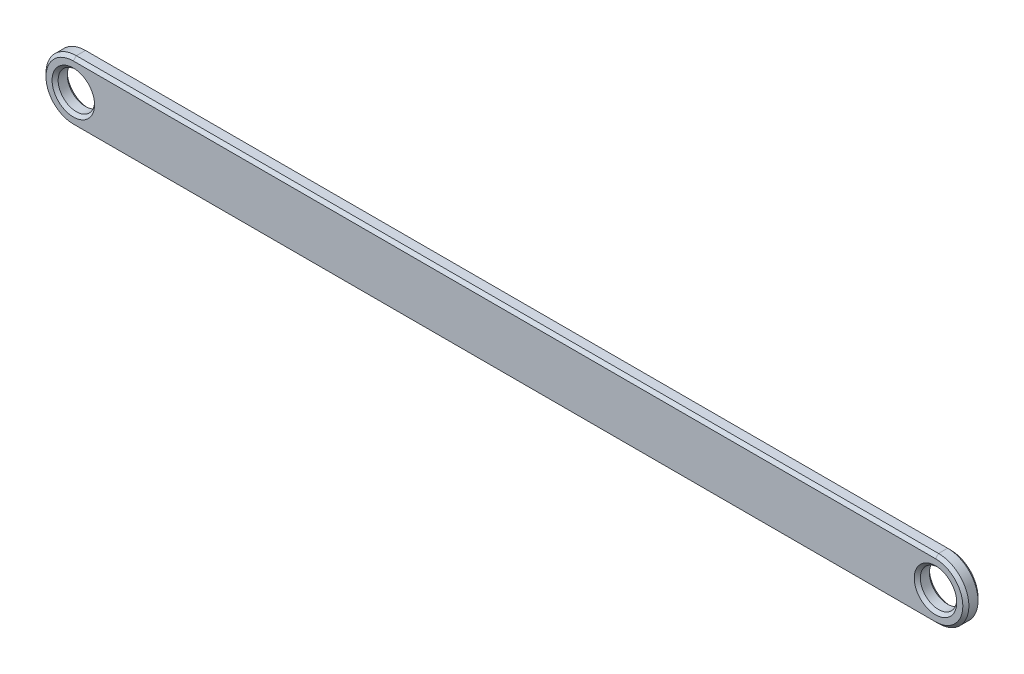
SolidWorks part; units mm, degrees
ref_plane "Front Plane" through (0, 0, 0) normal (0, 0, 1) x (1, 0, 0)
ref_plane "Top Plane" through (0, 0, 0) normal (0, 1, 0) x (1, 0, 0)
ref_plane "Right Plane" through (0, 0, 0) normal (1, 0, 0) x (0, 0, -1)
sketch "Sketch1" plane through (0, 0, 0) normal (0, 0, 1) x (1, 0, 0)
  line L0 (0, 157.4916) -> (0, -223.2358) construction
  line L1 (710, -50) -> (-710, -50)
  line L3 (710, 50) -> (-710, 50)
  line L4 (-710, 0) -> (710, 0) construction
  arc A0 (-710, 50) -> (-710, -50) centre (-710, 0) ccw
  circle A1 centre (-710, 0) radius 30
  arc A2 (710, 50) -> (710, -50) centre (710, 0) cw
  circle A3 centre (710, 0) radius 30
  point P0 (0, 0)
  point P12 (0, 0)
  point P13 (-451.3779, -167.3853)
  point P14 (-602.1707, 50)
  dimension "D1" = 60
  dimension "D2" = 20
  dimension "D3" = 1420
extrude "Boss-Extrude1" add sketch "Sketch1" along normal blind 25
chamfer "Chamfer1" distance 5 angle 45 12 edges at (680, 0, 0) (-680, 0, 0) (0, -50, 0) (760, 0, 0) (0, 50, 0) (-760, 0, 0) (680, 0, 25) (0, 50, 25) (760, 0, 25) (0, -50, 25) (-760, 0, 25) (-680, 0, 25)
equation "\"length\"= 1420"
equation "\"D3@Sketch1\"=\"length\""
